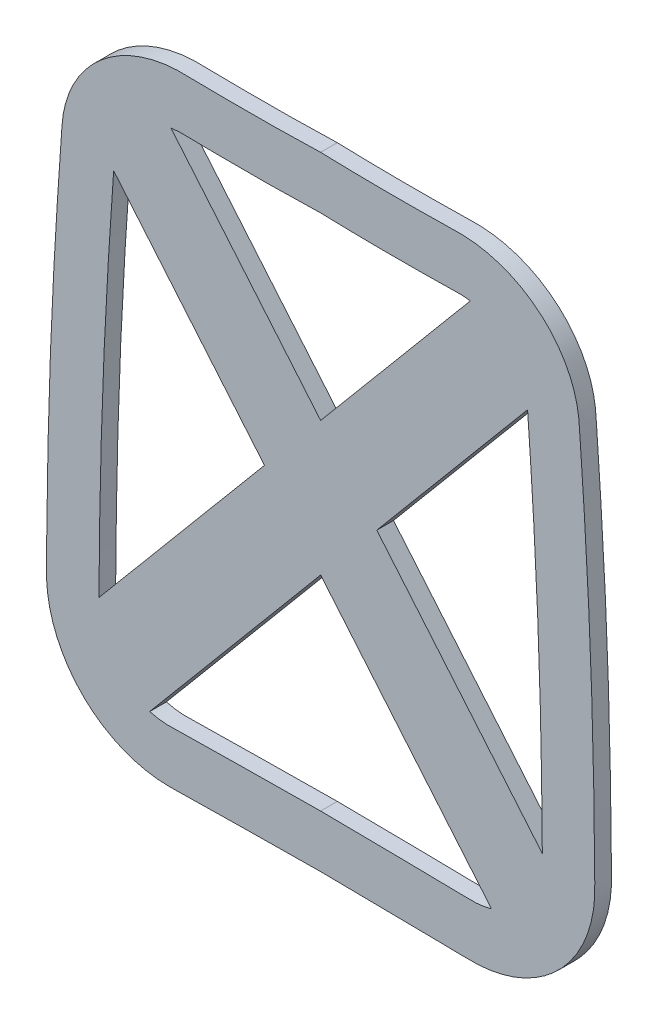
SolidWorks part; units mm, degrees
material "Фанера"
ref_plane "Front Plane" through (0, 0, 0) normal (0, 0, 1) x (1, 0, 0)
ref_plane "Top Plane" through (0, 0, 0) normal (0, 1, 0) x (1, 0, 0)
ref_plane "Right Plane" through (0, 0, 0) normal (1, 0, 0) x (0, 0, -1)
sketch "Эскиз1" plane through (0, 0, 0) normal (0, 0, 1) x (1, 0, 0)
  line L0 (-34.9049, 115.8134) -> (76.0792, 115.8134) construction
  line L1 (-27.3006, 129.2024) -> (-27.3006, 19.6546) construction
  line L2 (-34.9049, 115.8134) -> (-9.4168, 85.4379)
  line L3 (-27.3006, 129.2024) -> (0.0027, 96.6636)
  line L4 (0.0027, 180.1242) -> (0.0027, -33.4343) construction
  line L5 (34.9103, 115.8134) -> (9.4222, 85.4379)
  line L6 (27.306, 129.2024) -> (0.0027, 96.6636)
  line L7 (-9.4168, 85.4379) -> (-39.9802, 49.0138)
  line L8 (0.0027, 74.2122) -> (-30.7301, 37.5862)
  line L9 (9.4222, 85.4379) -> (39.9856, 49.0138)
  line L10 (0.0027, 74.2122) -> (30.7355, 37.5862)
  line L11 (-34.9049, 115.8134) -> (-36.3691, 125.532)
  line L12 (-36.3691, 125.532) -> (-27.3006, 129.2024)
  line L13 (-30.7301, 37.5862) -> (-37.4833, 41.3904)
  line L14 (-37.4833, 41.3904) -> (-39.9802, 49.0138)
  line L15 (30.7355, 37.5862) -> (38.6836, 40.1895)
  line L16 (38.6836, 40.1895) -> (39.9856, 49.0138)
  line L17 (27.306, 129.2024) -> (36.5404, 124.0005)
  line L18 (36.5404, 124.0005) -> (34.9103, 115.8134)
  spline S2 degree 3 poles (0, 31.9238) (1.8097, 31.9073) (5.4292, 31.8743) (9.9245, 31.8213) (13.5438, 31.7731) (15.7952, 31.7408) (17.6338, 31.7123) (19.0091, 31.6896) (20.3768, 31.6659) (21.5365, 31.6451) (22.4725, 31.6283) (23.2126, 31.615) (23.928, 31.6022) (24.6186, 31.5902) (25.2844, 31.5782) (25.9252, 31.5893) (26.5403, 31.6178) (27.2511, 31.6716) (28.0561, 31.7627) (28.9521, 31.9057) (30.4219, 32.2087) (32.4402, 32.819) (34.9088, 33.953) (37.1933, 35.4108) (39.2613, 37.1722) (41.0616, 39.1951) (42.58, 41.4616) (43.6361, 43.628) (44.3422, 45.6235) (44.7934, 47.3819) (45.0725, 49.1141) (45.2071, 50.8635) (45.1833, 52.6791) (45.1727, 54.5539) (45.1546, 56.431) (45.1355, 58.2504) (45.1097, 60.3585) (45.0632, 63.6504) (44.9984, 67.2887) (44.8981, 71.8653) (44.7772, 76.4706) (44.6005, 81.9262) (44.3878, 87.3806) (44.1374, 92.8331) (43.8976, 97.3982) (43.6899, 101.0309) (43.4692, 104.7044) (43.1795, 109.2208) (42.8989, 113.3068) (42.7098, 115.988) (42.6336, 117.0487) (42.579, 117.8207) (42.5406, 118.3217) (42.4789, 118.8628) (42.3935, 119.4443) (42.1838, 120.5817) (41.7647, 122.1057) (41.069, 123.8082) (40.2182, 125.4377) (39.1436, 127.0628) (37.4411, 129.0606) (35.2183, 130.9882) (32.5133, 132.6183) (29.8305, 133.7254) (27.773, 134.2623) (26.3395, 134.5082) (25.5209, 134.6146) (24.7219, 134.6871) (23.9439, 134.728) (23.1883, 134.7412) (22.4563, 134.7247) (21.5114, 134.7063) (20.3537, 134.6855) (18.983, 134.6649) (17.6353, 134.6484) (15.8367, 134.6313) (13.583, 134.6199) (9.9595, 134.6235) (6.3545, 134.6622) (2.7323, 134.7366) (0.9218, 134.7899) (0, 134.817) knots 0 0 0 0 0.031122 0.062244 0.077307 0.093366 0.100964 0.108927 0.117019 0.124488 0.128873 0.133116 0.137218 0.141177 0.144994 0.148667 0.152197 0.15558 0.160924 0.166123 0.171177 0.186725 0.202257 0.217751 0.233178 0.248825 0.264167 0.279952 0.290128 0.300525 0.311125 0.32026 0.330659 0.342333 0.352506 0.362937 0.373621 0.388761 0.419551 0.436194 0.467482 0.49877 0.53006 0.561346 0.592632 0.608669 0.623918 0.655915 0.686494 0.694347 0.702136 0.70478 0.707656 0.710776 0.714143 0.717762 0.730662 0.74123 0.749331 0.762244 0.774636 0.794377 0.812537 0.828712 0.844125 0.848987 0.853718 0.858316 0.862781 0.867112 0.871308 0.875371 0.883363 0.891219 0.898944 0.906541 0.922149 0.9377 0.968851 0.984142 1 1 1 1 construction
  spline S3 degree 3 poles (0, 134.817) (-0.6237, 134.7982) (-1.8561, 134.7611) (-3.6828, 134.7172) (-5.7899, 134.6757) (-8.2108, 134.642) (-10.9495, 134.6222) (-13.6989, 134.6201) (-16.4234, 134.6347) (-19.1654, 134.6656) (-21.1981, 134.6997) (-22.5447, 134.7269) (-23.18, 134.74) (-23.8335, 134.7304) (-24.5044, 134.7003) (-25.1919, 134.6469) (-25.8951, 134.5687) (-26.6129, 134.4637) (-27.9657, 134.2165) (-29.9645, 133.6785) (-32.1908, 132.7433) (-34.0559, 131.6932) (-35.9973, 130.3485) (-38.2438, 128.2806) (-40.1154, 125.7127) (-41.4886, 122.9481) (-42.14, 120.8713) (-42.4433, 119.165) (-42.5509, 118.2556) (-42.6086, 117.3874) (-42.672, 116.5198) (-42.7364, 115.6085) (-42.9052, 113.2181) (-43.1763, 109.267) (-43.4675, 104.7316) (-43.6892, 101.0425) (-43.8978, 97.3941) (-44.1386, 92.8096) (-44.3898, 87.3344) (-44.6029, 81.858) (-44.7799, 76.3807) (-44.9008, 71.7574) (-44.9803, 68.1049) (-45.0332, 65.3363) (-45.0774, 62.6547) (-45.1118, 60.2045) (-45.1373, 58.0875) (-45.1565, 56.2607) (-45.1692, 54.8433) (-45.1775, 53.8277) (-45.1821, 53.2063) (-45.1866, 52.6063) (-45.1899, 52.0277) (-45.1952, 51.4704) (-45.1862, 50.9342) (-45.1642, 50.4194) (-45.131, 49.9266) (-45.0882, 49.456) (-44.9474, 48.2199) (-44.5597, 46.2465) (-43.6611, 43.6407) (-42.4473, 41.2401) (-40.9287, 39.0277) (-39.1221, 37.0371) (-37.0316, 35.2919) (-34.7244, 33.8531) (-32.6453, 32.9253) (-30.9211, 32.361) (-29.6141, 32.0298) (-28.2796, 31.7859) (-27.1158, 31.6539) (-26.1106, 31.5938) (-25.2765, 31.5759) (-24.4, 31.5946) (-23.4814, 31.6099) (-22.5206, 31.6275) (-21.4359, 31.6469) (-20.2046, 31.6689) (-18.8471, 31.6924) (-17.4829, 31.7147) (-15.6613, 31.7427) (-13.4301, 31.7747) (-9.8414, 31.8224) (-5.383, 31.8747) (-1.7943, 31.9074) (0, 31.9238) knots 0 0 0 0 0.010731 0.021203 0.031422 0.046974 0.062838 0.078519 0.094255 0.109693 0.125675 0.129214 0.132856 0.136601 0.140451 0.144403 0.148459 0.152616 0.156875 0.172106 0.188102 0.198261 0.208868 0.22866 0.250469 0.263071 0.281641 0.287626 0.292864 0.29738 0.302588 0.307824 0.31309 0.343796 0.37593 0.391245 0.407352 0.438774 0.470192 0.501607 0.53302 0.564433 0.581141 0.595846 0.612052 0.627261 0.637986 0.64846 0.658679 0.662363 0.665925 0.669365 0.672682 0.675875 0.678949 0.681903 0.684735 0.687443 0.690027 0.706129 0.7219 0.737288 0.752246 0.767915 0.783365 0.798929 0.81453 0.822382 0.830107 0.837698 0.845695 0.850231 0.855013 0.860038 0.865305 0.870814 0.876562 0.883961 0.891993 0.89991 0.907424 0.923324 0.938283 0.969142 1 1 1 1 construction
  spline S4 degree 1 poles (0, 31.1237) (-0.0003, 135.6173) knots 0 0 1 1 construction
  spline S5 degree 1 poles (-0.0003, 135.6173) (0, 31.1237) knots 0 0 1 1 construction
  spline S6 degree 3 poles (0, 31.1237) (3.6337, 31.0906) (9.0834, 31.0352) (15.444, 30.9472) (19.0732, 30.8888) (21.8072, 30.8415) (24.0503, 30.7958) (25.9263, 30.774) (28.7568, 30.9572) (32.9377, 31.9363) (37.9496, 34.7244) (42.0033, 38.7774) (44.7967, 43.7861) (45.7984, 47.9465) (45.9969, 50.7893) (45.9892, 52.6536) (45.9689, 54.9017) (45.943, 57.6379) (45.8991, 61.2723) (45.8282, 65.82) (45.7146, 71.2751) (45.5699, 76.7303) (45.3325, 84.003) (45.0217, 91.2738) (44.638, 98.5401) (44.3171, 103.9878) (44.0256, 108.5248) (43.7797, 112.1547) (43.623, 114.4192) (43.4931, 116.2389) (43.4003, 117.5822) (43.2873, 119.0017) (42.9559, 120.8802) (42.2663, 123.1666) (40.6001, 126.5968) (37.5767, 130.3225) (33.6237, 133.0209) (30.1225, 134.4726) (27.3724, 135.1982) (25.0364, 135.4976) (23.1311, 135.5492) (21.3123, 135.4957) (19.0464, 135.466) (15.4171, 135.4227) (10.882, 135.4148) (5.4406, 135.4695) (1.8131, 135.564) (-0.0003, 135.6173) knots 0.000042 0.000042 0.000042 0.000042 0.062548 0.093801 0.109427 0.125054 0.14068 0.148493 0.156307 0.18756 0.218813 0.250065 0.281318 0.312571 0.320385 0.328198 0.343824 0.359451 0.375077 0.40633 0.437583 0.468836 0.500089 0.562595 0.593848 0.625101 0.656354 0.67198 0.687607 0.69542 0.703233 0.711047 0.71886 0.734486 0.750113 0.781366 0.812619 0.828245 0.843872 0.859498 0.867311 0.875125 0.890751 0.906378 0.937631 0.968884 1.000137 1.000137 1.000137 1.000137
  spline S7 degree 3 poles (-0.0003, 135.6173) (-1.8135, 135.5627) (-5.4406, 135.4701) (-10.8815, 135.4146) (-15.4165, 135.4227) (-19.0458, 135.4659) (-21.3113, 135.4957) (-23.1301, 135.5492) (-25.0355, 135.4977) (-27.3713, 135.1984) (-30.121, 134.4732) (-33.623, 133.021) (-37.5701, 130.329) (-40.6008, 126.5963) (-42.2667, 123.1654) (-42.9569, 120.8762) (-43.2878, 118.9981) (-43.4008, 117.5759) (-43.4936, 116.2356) (-43.6231, 114.4155) (-43.7803, 112.1512) (-44.0257, 108.5213) (-44.3173, 103.9846) (-44.6382, 98.5371) (-45.0218, 91.271) (-45.3326, 84.0004) (-45.5699, 76.728) (-45.7146, 71.273) (-45.8282, 65.8181) (-45.8992, 61.2706) (-45.9429, 57.6362) (-45.9695, 54.9009) (-45.9868, 52.6514) (-45.9973, 50.7856) (-45.7975, 47.9505) (-44.7955, 43.7804) (-42.0016, 38.776) (-37.9477, 34.7227) (-32.9349, 31.9354) (-28.7557, 30.9571) (-25.9256, 30.774) (-24.0472, 30.7955) (-21.8073, 30.8417) (-19.0723, 30.8887) (-15.4436, 30.9473) (-9.083, 31.0352) (-3.6336, 31.0906) (0, 31.1237) knots -0.000137 -0.000137 -0.000137 -0.000137 0.031116 0.062369 0.093622 0.109249 0.124875 0.132689 0.140502 0.156128 0.171755 0.187381 0.218634 0.249887 0.265514 0.28114 0.288953 0.296767 0.30458 0.312393 0.32802 0.343646 0.374899 0.406152 0.437405 0.499911 0.531164 0.562417 0.59367 0.624923 0.640549 0.656176 0.671802 0.679615 0.687429 0.718682 0.749935 0.781187 0.81244 0.843693 0.851507 0.85932 0.874946 0.890573 0.906199 0.937452 0.999958 0.999958 0.999958 0.999958
  spline S8 degree 1 poles (0, 39.9241) (0.0027, 126.8134) knots 0 0 1 1 construction
  spline S9 degree 1 poles (0.0027, 126.8134) (0, 39.9241) knots 0 0 1 1 construction
  spline S10 degree 3 poles (0, 39.9241) (1.8189, 39.9075) (5.4538, 39.8745) (10.0125, 39.8209) (13.6532, 39.7724) (16.3857, 39.7331) (18.6683, 39.6968) (20.4917, 39.6651) (21.8558, 39.6407) (22.9896, 39.6203) (23.8975, 39.604) (24.4572, 39.5943) (24.9231, 39.5858) (25.1958, 39.5819) (25.3832, 39.5818) (25.659, 39.5866) (26.0181, 39.6014) (26.5666, 39.6424) (27.2509, 39.7277) (28.3129, 39.9346) (29.6173, 40.3307) (31.092, 41.0121) (32.9103, 42.1794) (34.4564, 43.7058) (35.6552, 45.5178) (36.3626, 46.9902) (36.7834, 48.3002) (37.0101, 49.3622) (37.1294, 50.1976) (37.1805, 50.8631) (37.1934, 51.4108) (37.1922, 52.1456) (37.1785, 53.3577) (37.171, 54.6927) (37.158, 56.0396) (37.1395, 57.8497) (37.1128, 60.0994) (37.0741, 62.8045) (37.0137, 66.4074) (36.8834, 72.7102) (36.6735, 79.9039) (36.3929, 87.0879) (36.1453, 92.4744) (35.8621, 97.8628) (35.5984, 102.3551) (35.3727, 105.9518) (35.1967, 108.6503) (35.0448, 110.9007) (34.9206, 112.7021) (34.8262, 114.0553) (34.747, 115.1791) (34.6825, 116.0804) (34.6338, 116.7616) (34.5847, 117.4571) (34.5595, 117.7121) (34.506, 118.1008) (34.4231, 118.5526) (34.2798, 119.1404) (33.9752, 120.0558) (33.451, 121.1739) (32.6024, 122.4353) (31.2054, 123.9605) (29.4432, 125.2021) (27.4341, 126.0629) (26.097, 126.4331) (24.9993, 126.6224) (24.3057, 126.6959) (23.7386, 126.7277) (23.3171, 126.7386) (22.9163, 126.7336) (22.1654, 126.7172) (21.4912, 126.7048) (20.5653, 126.6882) (19.4137, 126.6702) (18.0296, 126.6522) (16.1832, 126.6336) (13.8743, 126.6205) (10.1746, 126.6219) (6.4826, 126.6593) (2.7596, 126.7333) (0.9237, 126.7864) (0.0027, 126.8134) knots -0.000418 -0.000418 -0.000418 -0.000418 0.030803 0.062023 0.077633 0.093243 0.108854 0.116659 0.124464 0.132269 0.136172 0.140074 0.142025 0.143977 0.145928 0.147879 0.151782 0.155684 0.163489 0.171295 0.186905 0.202515 0.218125 0.249346 0.264956 0.280566 0.296176 0.303981 0.311787 0.319592 0.323494 0.327397 0.335202 0.343007 0.350812 0.358617 0.374227 0.389838 0.405448 0.436668 0.499109 0.53033 0.56155 0.592771 0.623991 0.639601 0.655212 0.670822 0.678627 0.686432 0.694237 0.69814 0.702042 0.705945 0.709847 0.71375 0.717652 0.725458 0.733263 0.748873 0.764483 0.780093 0.811314 0.826924 0.842534 0.850339 0.858144 0.862047 0.86595 0.869852 0.873755 0.877657 0.88156 0.889365 0.89717 0.904975 0.920585 0.936196 0.967416 0.983026 0.998636 0.998636 0.998636 0.998636
  spline S11 degree 3 poles (0.0027, 126.8134) (-1.847, 126.7578) (-5.5462, 126.6672) (-10.1762, 126.6221) (-13.8731, 126.6204) (-16.1826, 126.6336) (-18.0289, 126.6522) (-19.4124, 126.6701) (-20.5655, 126.6882) (-21.487, 126.7045) (-22.0651, 126.7156) (-22.5224, 126.7247) (-22.8716, 126.7321) (-23.1332, 126.7364) (-23.3747, 126.7366) (-23.7444, 126.7277) (-24.3003, 126.6961) (-25.0001, 126.6224) (-26.0953, 126.4333) (-27.4334, 126.0633) (-29.443, 125.202) (-31.2027, 123.9631) (-32.5999, 122.4381) (-33.453, 121.1706) (-34.0786, 119.8359) (-34.3809, 118.7881) (-34.5073, 118.0907) (-34.5487, 117.7953) (-34.5741, 117.5612) (-34.5896, 117.3858) (-34.6089, 117.1225) (-34.6415, 116.6461) (-34.6838, 116.0666) (-34.7464, 115.1864) (-34.8268, 114.0462) (-34.9209, 112.6995) (-35.0451, 110.8971) (-35.1968, 108.6474) (-35.3729, 105.9483) (-35.5986, 102.352) (-35.8622, 97.8598) (-36.1454, 92.4716) (-36.393, 87.0853) (-36.6736, 79.9016) (-36.8835, 72.7079) (-37.0138, 66.4057) (-37.0742, 62.8024) (-37.1128, 60.099) (-37.1396, 57.8451) (-37.158, 56.042) (-37.1704, 54.6885) (-37.1792, 53.563) (-37.1852, 52.7695) (-37.188, 52.3288) (-37.1903, 51.969) (-37.1932, 51.6369) (-37.1929, 51.3567) (-37.1804, 50.8748) (-37.1071, 49.9065) (-36.8662, 48.5563) (-36.3622, 46.9899) (-35.654, 45.5156) (-34.4558, 43.7052) (-32.9083, 42.1779) (-31.0915, 41.0118) (-29.6145, 40.3299) (-28.3144, 39.9346) (-27.2472, 39.7275) (-26.4404, 39.6255) (-25.7119, 39.5851) (-25.2084, 39.5799) (-24.7148, 39.5895) (-24.2321, 39.5984) (-23.7763, 39.6062) (-22.9944, 39.62) (-21.8525, 39.6408) (-20.4918, 39.6651) (-18.6673, 39.6968) (-16.3852, 39.7331) (-13.6527, 39.7724) (-10.0121, 39.8209) (-5.4536, 39.8744) (-1.8189, 39.9075) (0, 39.9241) knots 0.001363 0.001363 0.001363 0.001363 0.032584 0.063804 0.079414 0.095024 0.10283 0.110635 0.11844 0.122342 0.126245 0.128196 0.130147 0.132099 0.13405 0.137953 0.141855 0.14966 0.157465 0.173076 0.188686 0.219906 0.235517 0.251127 0.266737 0.282347 0.28625 0.290152 0.292104 0.294055 0.296006 0.297957 0.30186 0.305763 0.313568 0.321373 0.329178 0.344788 0.360398 0.376009 0.407229 0.43845 0.46967 0.500891 0.563331 0.594552 0.610162 0.625772 0.641383 0.649188 0.656993 0.664798 0.668701 0.670652 0.672603 0.674554 0.676506 0.680408 0.688213 0.703824 0.719434 0.735044 0.750654 0.781875 0.797485 0.813095 0.828705 0.83651 0.844316 0.852121 0.856023 0.859926 0.861877 0.863828 0.867731 0.875536 0.883341 0.891146 0.906757 0.922367 0.937977 0.969197 1.000418 1.000418 1.000418 1.000418
  point P13 (0.0027, 96.6636)
  point P15 (0.0027, 74.2122)
  point P16 (0.0027, 96.6636)
  point P17 (0.0027, 74.2122)
  dimension "D3" = 11
  dimension "D4" = 50
  dimension "D1" = 0.8
  dimension "D2" = 8
extrude "Бобышка-Вытянуть1" add sketch "Эскиз1" along normal mid plane 2.8 contours L3 S11 L2 L7 L8 L10 S10 L9 L5 L6 | S6 S7 S11 S10 L6 L17 L18 L5 L9 L16 L15 L10 L8 L13 L14 L7 L2 L11 L12 L3 | S11 L3 L12 L11 L2 | S11 L7 L14 L13 L8 | S10 L10 L15 L16 L9 | S10 L5 L18 L17 L6
